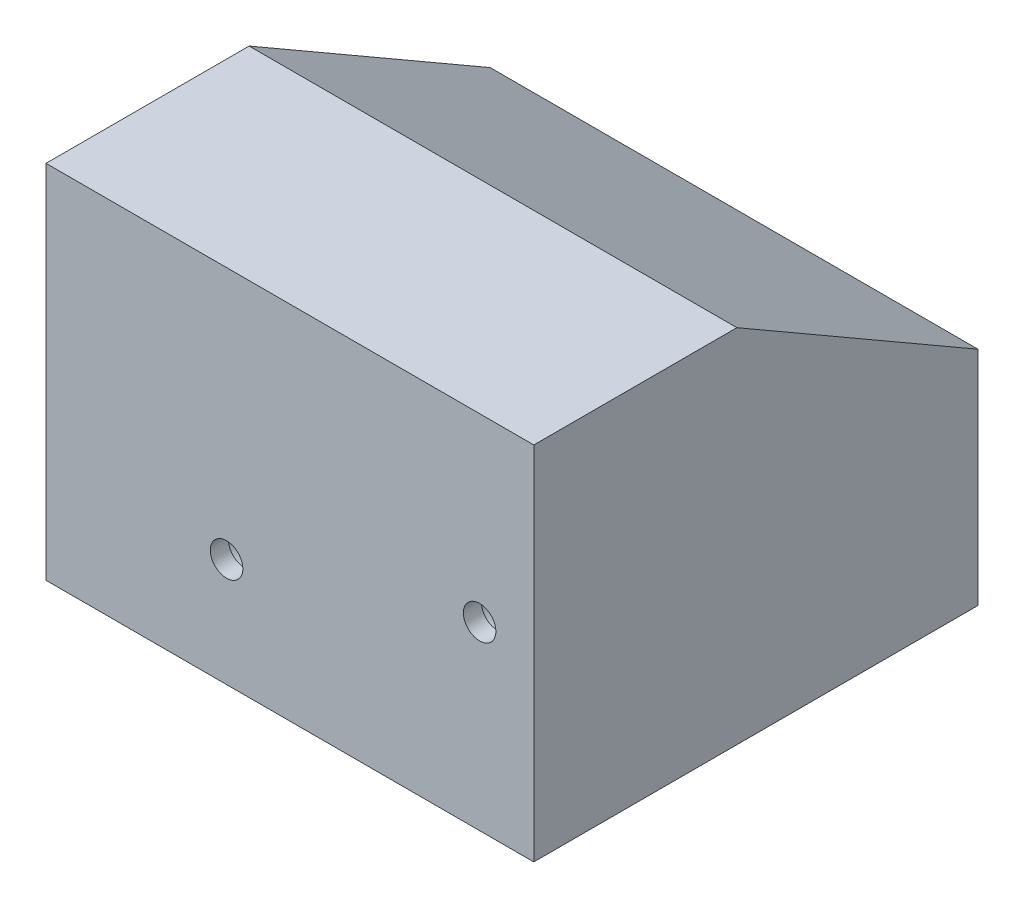
SolidWorks part; units mm, degrees
ref_plane "Ebene vorne" through (0, 0, 0) normal (0, 0, 1) x (1, 0, 0)
ref_plane "Ebene oben" through (0, 0, 0) normal (0, 1, 0) x (1, 0, 0)
ref_plane "Ebene rechts" through (0, 0, 0) normal (1, 0, 0) x (0, 0, -1)
sketch "Skizze1" plane through (0, 0, 0) normal (0, 0, 1) x (1, 0, 0)
  line L1 (67.5347, -50) -> (-67.5347, -50)
  line L2 (67.5347, -50) -> (67.5347, 50)
  line L3 (67.5347, 50) -> (-67.5347, 50)
  line L4 (-67.5347, -50) -> (-67.5347, 50)
  line L5 (67.5347, -50) -> (-67.5347, 50) construction
  line L6 (67.5347, 50) -> (-67.5347, -50) construction
  point P0 (0, 0)
  dimension "D1" = 100
  dimension "D2" = 135.0694
extrude "Aufsatz-Linear austragen1" add sketch "Skizze1" along normal blind 123
sketch "Skizze2" plane through (-67.5347, 0, 0) normal (-1, 0, 0) x (0, 0, 1)
  line L0 (0, 11.4583) -> (66.7561, 50)
  line L1 (0, 50) -> (0, -50) construction
  line L2 (123, 50) -> (0, 50) construction
  line L3 (0, 11.4583) -> (0, 71.7779)
  line L4 (0, 71.7779) -> (66.7561, 50)
  dimension "D1" = 77.0833
  dimension "D2" = 30
extrude "Schnitt-Linear austragen1" cut sketch "Skizze2" against normal through all contours L4 L0 L3
sketch "Skizze3" plane through (0, 0, 0) normal (0, 0, -1) x (-1, 0, 0)
  line L0 (67.5347, 11.4583) -> (67.5347, -50) construction
  line L1 (67.5347, -50) -> (-67.5347, -50) construction
  line L2 (-67.5347, -50) -> (-67.5347, 11.4583) construction
  circle A0 centre (-52.5347, 0) radius 10.3482
  circle A1 centre (17.5347, -20) radius 14.5236
  dimension "D1" = 50
  dimension "D2" = 30
  dimension "D3" = 50
  dimension "D4" = 15
hole_wizard "Stirnsenkung für M8 Senkschraube (Kopf Button)1" positions "Skizze5" profile "Skizze4" counterbore size "M8" standard "ANSI Metrisch" end condition through all
sketch "Skizze5" plane through (0, 0, 0) normal (0, 0, -1) x (-1, 0, 0)
  point P0 (-52.5347, 0)
  point P3 (17.5347, -20)
sketch "Skizze4" plane through (52.5347, 0, 0) normal (1, 0, 0) x (0, 1, 0)
  line L0 (0, 0) -> (0, 123)
  line L1 (0, 123) -> (4.5, 123)
  line L3 (4.5, 123) -> (4.5, 118)
  line L4 (4.5, 118) -> (7.5, 118)
  line L5 (7.5, 118) -> (7.5, 0)
  line L7 (7.5, 0) -> (0, 0)
  line L11 (0, -6.35) -> (0, 107.95) construction
  dimension "Bohrerdurchmesser" = 9
  dimension "Bohrungstiefe" = 123
  dimension "Senkdurchmesser2" = 15
  dimension "Senktiefe2" = 118
